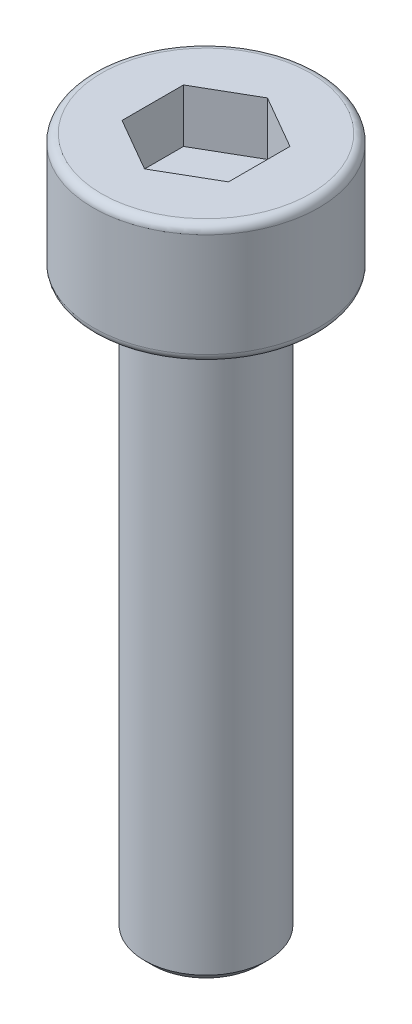
SolidWorks part; units mm, degrees
material "不锈钢 (铁素体)"
ref_plane "前视基准面" through (0, 0, 0) normal (0, 0, 1) x (1, 0, 0)
ref_plane "上视基准面" through (0, 0, 0) normal (0, 1, 0) x (1, 0, 0)
ref_plane "右视基准面" through (0, 0, 0) normal (1, 0, 0) x (0, 0, -1)
sketch "草图1" plane through (0, 0, 0) normal (0, 0, 1) x (1, 0, 0)
  line L0 (0, 0) -> (0, -21.235) construction
  line L1 (0, 0) -> (2.75, 0)
  line L2 (2.75, 0) -> (2.75, -2.93)
  line L3 (2.75, -2.93) -> (1.5, -2.93)
  line L4 (1.5, -2.93) -> (1.5, -16.93)
  line L5 (1.5, -16.93) -> (0, -16.93)
  line L6 (0, -16.93) -> (0, 0)
  point P5 (2.125, -2.93)
  dimension "D1" = 2.93
  dimension "D2" = 5.5
  dimension "D3" = 3
  dimension "D4" = 14
revolve "旋转1" add sketch "草图1" angle 360 about L0
cosmetic thread "装饰螺纹线1" parameters "D2"=2.459
sketch "草图2" plane through (0, 0, 0) normal (0, 1, 0) x (1, 0, 0)
  line L1 (0, 1.5) -> (-1.299, 0.75)
  line L2 (-1.299, 0.75) -> (-1.299, -0.75)
  line L3 (-1.299, -0.75) -> (0, -1.5)
  line L4 (0, -1.5) -> (1.299, -0.75)
  line L5 (1.299, -0.75) -> (1.299, 0.75)
  line L6 (1.299, 0.75) -> (0, 1.5)
  circle A0 centre (0, 0) radius 1.5 construction
  dimension "D1" = 3
extrude "切除-拉伸1" cut sketch "草图2" against normal blind 1.3
fillet "圆角1" radius 0.2 2 edges at (0, 0, 2.75) (0, -2.93, 2.75)
chamfer "倒角1" distance 0.2 angle 45 1 edges at (0, -16.93, 1.5)
